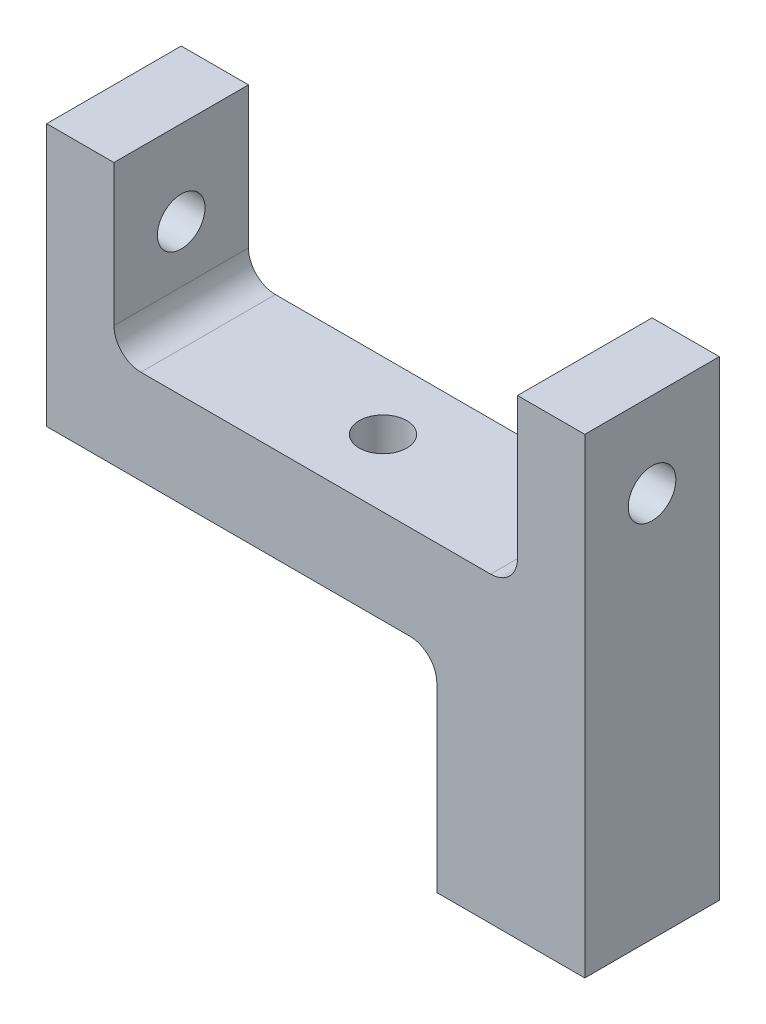
SolidWorks part; units mm, degrees
ref_plane "Front Plane" through (0, 0, 0) normal (0, 0, 1) x (1, 0, 0)
ref_plane "Top Plane" through (0, 0, 0) normal (0, 1, 0) x (1, 0, 0)
ref_plane "Right Plane" through (0, 0, 0) normal (1, 0, 0) x (0, 0, -1)
sketch "Sketch1" plane through (0, 0, 0) normal (0, 1, 0) x (1, 0, 0)
  line L1 (-25.4, -6.35) -> (25.4, -6.35)
  line L2 (-25.4, -6.35) -> (-25.4, 6.35)
  line L3 (-25.4, 6.35) -> (25.4, 6.35)
  line L4 (25.4, -6.35) -> (25.4, 6.35)
  line L5 (-25.4, -6.35) -> (25.4, 6.35) construction
  line L6 (-25.4, 6.35) -> (25.4, -6.35) construction
  point P0 (0, 0)
  dimension "D1" = 12.7
  dimension "D2" = 50.8
extrude "Boss-Extrude1" add sketch "Sketch1" along normal blind 44.45
sketch "Sketch2" plane through (0, 44.45, 0) normal (0, 1, 0) x (1, 0, 0)
  line L0 (25.4, -6.35) -> (25.4, 6.35) construction
  line L1 (-25.4, -152.4) -> (25.4, -152.4)
  line L2 (-25.4, -152.4) -> (-25.4, 0)
  line L3 (-25.4, 0) -> (25.4, 0)
  line L4 (25.4, -152.4) -> (25.4, 0)
  line L5 (-25.4, -152.4) -> (25.4, 0) construction
  line L6 (-25.4, 0) -> (25.4, -152.4) construction
  line L7 (-25.4, 6.35) -> (-25.4, -6.35) construction
  line L8 (25.4, 6.35) -> (-25.4, 6.35) construction
  point P0 (0, -76.2)
  dimension "D1" = 152.4
  dimension "D2" = 6.35
sketch "Sketch8" plane through (0, 0, 6.35) normal (0, 0, 1) x (1, 0, 0)
  line L1 (-11.43, -19.685) -> (11.43, -19.685)
  line L2 (-11.43, -19.685) -> (-11.43, 19.685)
  line L3 (-11.43, 19.685) -> (11.43, 19.685)
  line L4 (11.43, -19.685) -> (11.43, 19.685)
  line L5 (-11.43, -19.685) -> (11.43, 19.685) construction
  line L6 (-11.43, 19.685) -> (11.43, -19.685) construction
  line L7 (-19.05, 28.575) -> (19.05, 28.575)
  line L8 (-19.05, 28.575) -> (-19.05, 60.325)
  line L9 (-19.05, 60.325) -> (19.05, 60.325)
  line L10 (19.05, 28.575) -> (19.05, 60.325)
  line L11 (-19.05, 28.575) -> (19.05, 60.325) construction
  line L12 (-19.05, 60.325) -> (19.05, 28.575) construction
  line L13 (-11.43, 19.685) -> (-32.668, 19.685)
  line L14 (-11.43, 19.685) -> (-11.43, -19.685)
  line L15 (-11.43, -19.685) -> (-32.668, -19.685)
  line L16 (-32.668, 19.685) -> (-32.668, -19.685)
  point P0 (0, 0)
  point P6 (0, 44.45)
  line M5 (-25.4, 0) -> (25.4, 0)
  line M7 (25.4, 44.45) -> (-25.4, 44.45)
  line M8 (-25.4, 44.45) -> (-25.4, 0)
  dimension "D1" = 22.86
  dimension "155" = 39.37
  dimension "D3" = 31.75
  dimension "D4" = 38.1
extrude "Cut-Extrude1" cut sketch "Sketch8" against normal through all contours L2 L13 M8 M5 | L4 L3 L2 M5 | L7 L10 L8 M7
sketch "Sketch9" plane through (25.4, 0, 0) normal (1, 0, 0) x (0, 0, -1)
  point P0 (0, 36.4515)
hole_wizard "#8 Clearance Hole3" positions "Sketch9" profile "Sketch10" hole size "#8" standard "ANSI Inch" end condition through all
sketch "Sketch10" plane through (25.4, 36.4515, 0) normal (0, 1, 0) x (0, 0, -1)
  line L0 (0, 0) -> (0, 50.8)
  line L1 (0, 50.8) -> (2.2479, 50.8)
  line L2 (2.2479, 50.8) -> (2.2479, 0)
  line L5 (2.2479, 0) -> (0, 0)
  line L11 (0, -6.35) -> (0, 107.95) construction
  dimension "Thru Hole Dia." = 4.4958
  dimension "Thru Hole Depth" = 50.8
hole_wizard "#8 Clearance Hole2" positions "Sketch13" profile "Sketch14" hole size "#8" standard "ANSI Inch" end condition through all
sketch "Sketch13" plane through (0, 28.575, 0) normal (0, 1, 0) x (1, 0, 0)
  line L1 (-25.4, 0) -> (25.4, 0) construction
  point P8 (0, 0)
sketch "Sketch14" plane through (0, 28.575, 0) normal (1, 0, 0) x (0, 0, 1)
  line L0 (0, 0) -> (0, 28.575)
  line L1 (0, 28.575) -> (2.2479, 28.575)
  line L2 (2.2479, 28.575) -> (2.2479, 0)
  line L5 (2.2479, 0) -> (0, 0)
  line L11 (0, -6.35) -> (0, 107.95) construction
  dimension "Thru Hole Dia." = 4.4958
  dimension "Thru Hole Depth" = 28.575
hole_wizard "1/8 (0.18) Dowel Hole1" positions "Sketch15" profile "Sketch16" hole size "1/8" standard "ANSI Inch"
sketch "Sketch15" plane through (11.43, 0, 0) normal (-1, 0, 0) x (0, 0, 1)
  line L0 (-45.5977, 8.509) -> (-45.5977, 3.683) construction
  line L1 (-45.5977, 6.096) -> (0, 6.096) construction
  point P0 (0, 6.096)
sketch "Sketch16" plane through (11.43, 6.096, 0) normal (0, 1, 0) x (0, 0, 1)
  line L0 (0, 0) -> (0, 8.9936)
  line L1 (0, 8.9936) -> (2.286, 7.62)
  line L2 (2.286, 7.62) -> (2.286, 0)
  line L5 (2.286, 0) -> (0, 0)
  line L10 (0, 8.9936) -> (-2.286, 7.62) construction
  line L11 (0, -6.35) -> (0, 107.95) construction
  dimension "Hole Dia." = 4.572
  dimension "Hole Depth" = 7.62
  dimension "Drill Angle" = 118
fillet "Fillet1" radius 2.54 3 edges at (11.43, 19.685, 0) (-19.05, 28.575, 0) (19.05, 28.575, 0)
sketch "Sketch17" plane through (0, 44.45, 0) normal (0, 1, 0) x (1, 0, 0)
  line L1 (-25.4, 0) -> (25.4, 0)
  line L2 (-25.4, 0) -> (-25.4, -6.35)
  line L3 (-25.4, -6.35) -> (25.4, -6.35)
  line L4 (25.4, 0) -> (25.4, -6.35)
